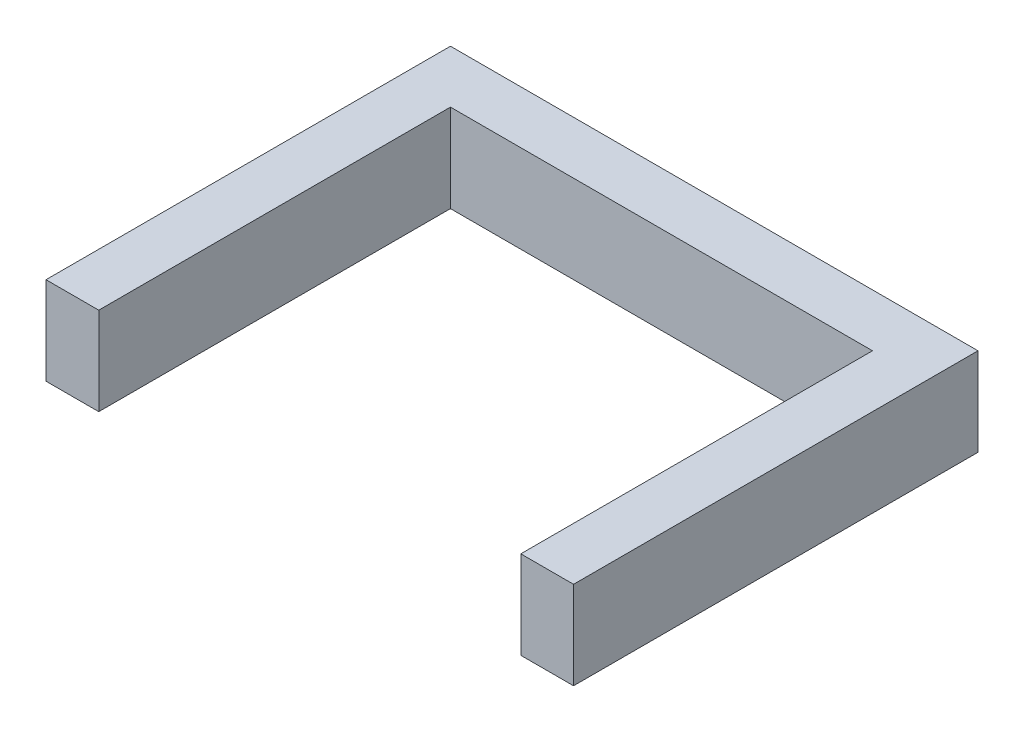
SolidWorks part; units mm, degrees
ref_plane "Front Plane" through (0, 0, 0) normal (0, 0, 1) x (1, 0, 0)
ref_plane "Top Plane" through (0, 0, 0) normal (0, 1, 0) x (1, 0, 0)
ref_plane "Right Plane" through (0, 0, 0) normal (1, 0, 0) x (0, 0, -1)
other "Configuration Table"
sketch "草图3" plane through (0, 0, 0) normal (0, 1, 0) x (1, 0, 0)
  line L0 (-15, 3) -> (15, 3)
  line L1 (15, 3) -> (15, -20)
  line L2 (15, -20) -> (12, -20)
  line L3 (12, -20) -> (12, 0)
  line L4 (12, 0) -> (-12, 0)
  line L5 (-12, 0) -> (-12, -20)
  line L6 (-12, -20) -> (-15, -20)
  line L7 (-15, -20) -> (-15, 3)
  point P2 (0, 0)
  point P9 (0, 0)
  point P10 (0, 0)
  point P12 (20.9304, -20)
  point P13 (0, 0)
  dimension "D1" = 20
  dimension "D2" = 3
  dimension "D3" = 23
  dimension "D4" = 24
extrude "凸台-拉伸2" add sketch "草图3" along normal blind 5
